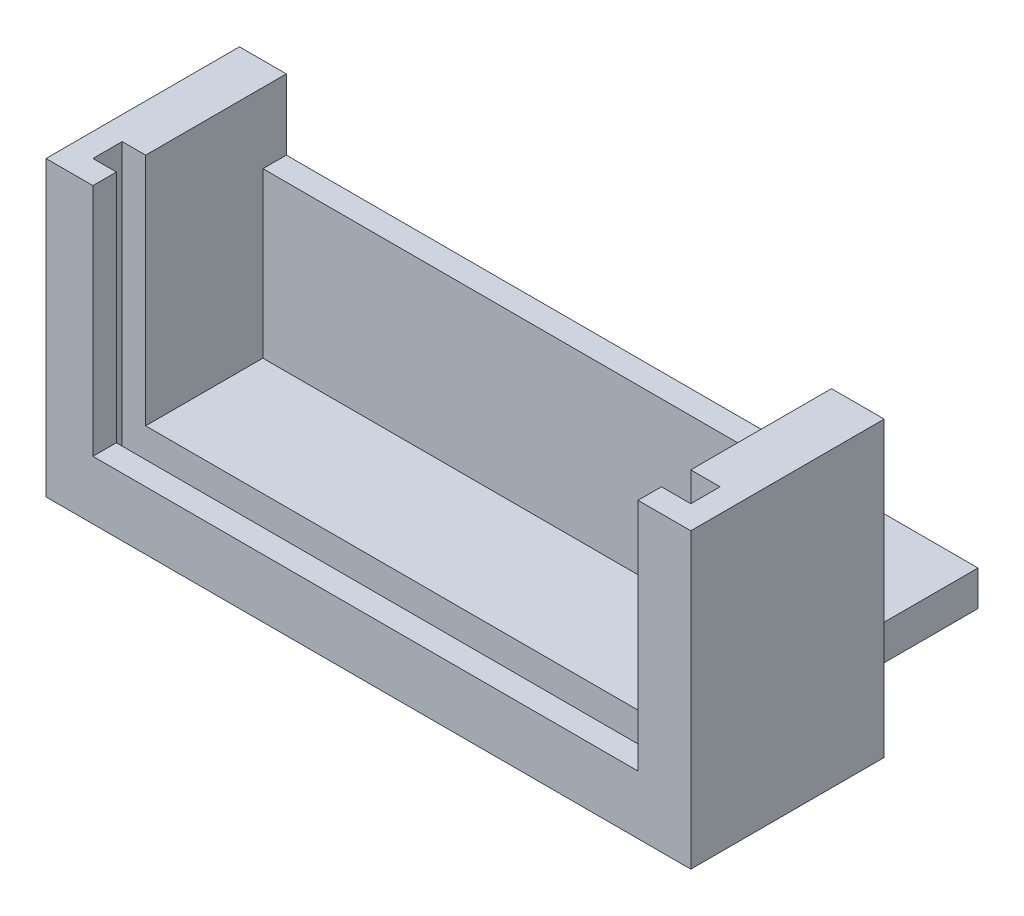
SolidWorks part; units mm, degrees
ref_plane "Front Plane" through (0, 0, 0) normal (0, 0, 1) x (1, 0, 0)
ref_plane "Top Plane" through (0, 0, 0) normal (0, 1, 0) x (1, 0, 0)
ref_plane "Right Plane" through (0, 0, 0) normal (1, 0, 0) x (0, 0, -1)
sketch "Sketch1" plane through (0, 0, 0) normal (0, 0, 1) x (1, 0, 0)
  line L0 (0, 0) -> (55, 0)
  line L1 (0, 0) -> (0, 25)
  line L2 (0, 25) -> (55, 25)
  line L3 (55, 0) -> (55, 25)
  dimension "D1" = 55
  dimension "D2" = 25
extrude "Boss-Extrude1" add sketch "Sketch1" along normal blind 16.5
sketch "Sketch2" plane through (0, 25, 0) normal (0, 1, 0) x (1, 0, 0)
  line L0 (0, -16.5) -> (0, 0) construction
  line L1 (2, -12) -> (4, -12)
  line L2 (2, -12) -> (2, -14.5)
  line L3 (2, -14.5) -> (4, -14.5)
  line L4 (53, -12) -> (53, -14.5)
  line L5 (55, -16.5) -> (55, 0) construction
  line L7 (55, -16.5) -> (0, -16.5) construction
  line L8 (55, 0) -> (0, 0) construction
  line L9 (4, -2) -> (50.5, -2)
  line L10 (4, -2) -> (4, -12)
  line L11 (4, -16.5) -> (50.5, -16.5)
  line L12 (50.5, -2) -> (50.5, -12)
  line L13 (4, -14.5) -> (4, -16.5)
  line L14 (50.5, -12) -> (53, -12)
  line L15 (50.5, -14.5) -> (53, -14.5)
  line L16 (50.5, -14.5) -> (50.5, -16.5)
  dimension "D1" = 2
  dimension "D2" = 2
  dimension "D3" = 2
  dimension "D4" = 2.5
  dimension "D5" = 2
  dimension "D6" = 2.5
  dimension "D7" = 2
extrude "Cut-Extrude1" cut sketch "Sketch2" against normal blind 20
sketch "Sketch3" plane through (0, 5, 0) normal (0, 1, 0) x (1, 0, 0)
  line L1 (2, -12) -> (53, -12)
  line L2 (2, -12) -> (2, -14.5)
  line L3 (2, -14.5) -> (53, -14.5)
  line L4 (53, -12) -> (53, -14.5)
extrude "Cut-Extrude2" cut sketch "Sketch3" against normal blind 2.5
sketch "Sketch4" plane through (0, 0, 0) normal (0, 0, -1) x (-1, 0, 0)
  line L0 (0, 0) -> (-55, 0) construction
  line L1 (-48, 0) -> (-7, 0)
  line L2 (-48, 0) -> (-48, 3)
  line L3 (-48, 3) -> (-7, 3)
  line L4 (-7, 0) -> (-7, 3)
  line L5 (-55, 0) -> (-55, 25) construction
  line L6 (0, 25) -> (0, 0) construction
  dimension "D1" = 7
  dimension "D2" = 7
  dimension "D3" = 3
extrude "Boss-Extrude2" add sketch "Sketch4" along normal blind 15
sketch "Sketch5" plane through (0, 0, 2) normal (0, 0, 1) x (1, 0, 0)
  line L0 (27.25, 25) -> (27.25, 19) construction
  line L1 (4, 25) -> (50.5, 25)
  line L2 (4, 25) -> (4, 19)
  line L3 (4, 19) -> (50.5, 19)
  line L4 (50.5, 25) -> (50.5, 19)
  line L5 (50.5, 25) -> (4, 25) construction
  line L6 (50.5, 5) -> (50.5, 25) construction
  point P8 (50, 21.7)
  dimension "D2" = 6
extrude "Cut-Extrude3" cut sketch "Sketch5" against normal blind 15
